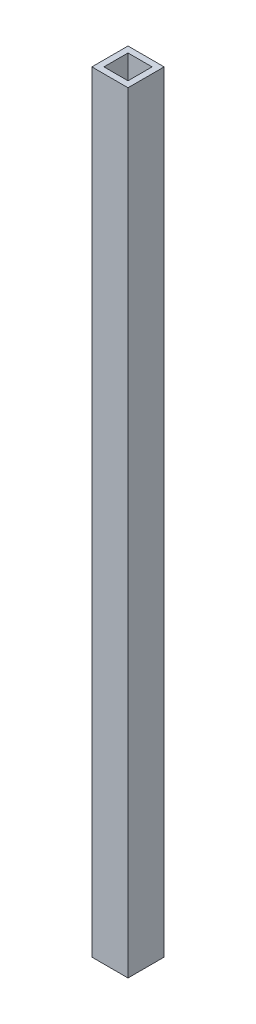
SolidWorks part; units mm, degrees
ref_plane "Front Plane" through (0, 0, 0) normal (0, 0, 1) x (1, 0, 0)
ref_plane "Top Plane" through (0, 0, 0) normal (0, 1, 0) x (1, 0, 0)
ref_plane "Right Plane" through (0, 0, 0) normal (1, 0, 0) x (0, 0, -1)
sketch "Sketch1" plane through (0, 0, 0) normal (0, 1, 0) x (1, 0, 0)
  line L1 (0, 0) -> (19.05, 0)
  line L2 (0, 0) -> (0, 19.05)
  line L3 (0, 19.05) -> (19.05, 19.05)
  line L4 (19.05, 0) -> (19.05, 19.05)
  dimension "D1" = 19.05
  dimension "D2" = 19.05
extrude "Boss-Extrude1" add sketch "Sketch1" along normal blind 406.4
sketch "Sketch2" plane through (0, 406.4, 0) normal (0, 1, 0) x (1, 0, 0)
  line L0 (19.05, 0) -> (19.05, 19.05) construction
  line L1 (3.175, 15.875) -> (15.875, 15.875)
  line L2 (3.175, 15.875) -> (3.175, 3.175)
  line L3 (3.175, 3.175) -> (15.875, 3.175)
  line L4 (15.875, 15.875) -> (15.875, 3.175)
  line L5 (19.05, 19.05) -> (0, 19.05) construction
  dimension "D1" = 12.7
  dimension "D2" = 12.7
  dimension "D3" = 3.175
  dimension "D4" = 3.175
extrude "Cut-Extrude1" cut sketch "Sketch2" against normal blind 406.4
